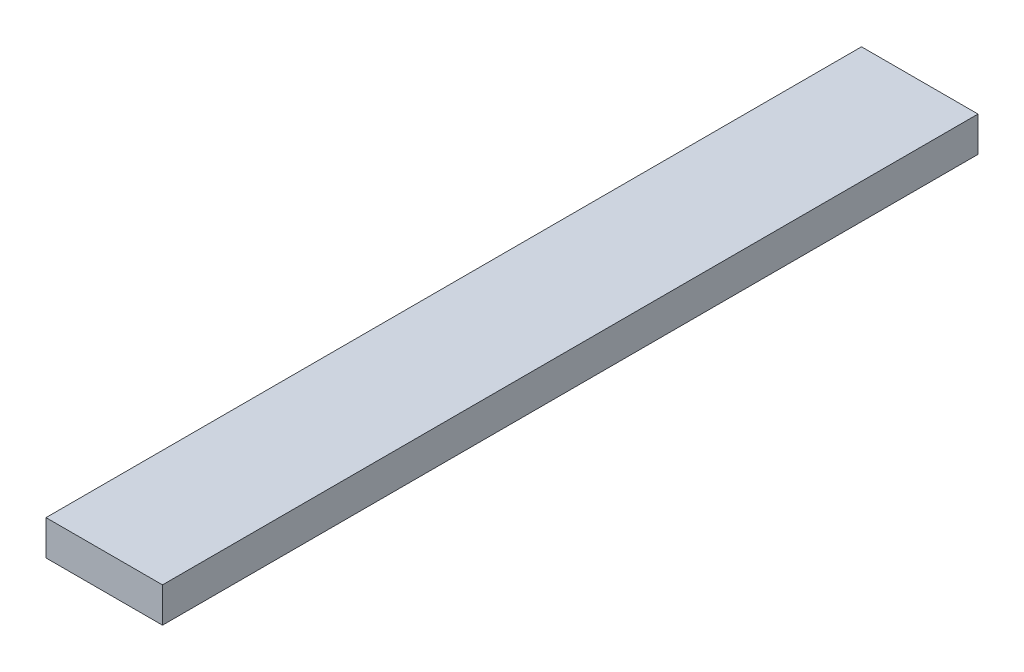
SolidWorks part; units mm, degrees
ref_plane "Front Plane" through (0, 0, 0) normal (0, 0, 1) x (1, 0, 0)
ref_plane "Top Plane" through (0, 0, 0) normal (0, 1, 0) x (1, 0, 0)
ref_plane "Right Plane" through (0, 0, 0) normal (1, 0, 0) x (0, 0, -1)
ref_plane "Plane4" through (0, -16.3, 0) normal (0, -1, 0) x (1, 0, 0)
sketch "Sketch1" plane through (0, -16.3, 0) normal (0, -1, 0) x (1, 0, 0)
  line L0 (-22.8575, -57.246) -> (-12.8575, -57.246)
  line L1 (-12.8575, -57.246) -> (-12.8575, 12.754)
  line L2 (-12.8575, 12.754) -> (-22.8575, 12.754)
  line L3 (-22.8575, 12.754) -> (-22.8575, -57.246)
  dimension "D1" = 70
  dimension "D2" = 10
extrude "Boss-Extrude1" add sketch "Sketch1" against normal blind 3
